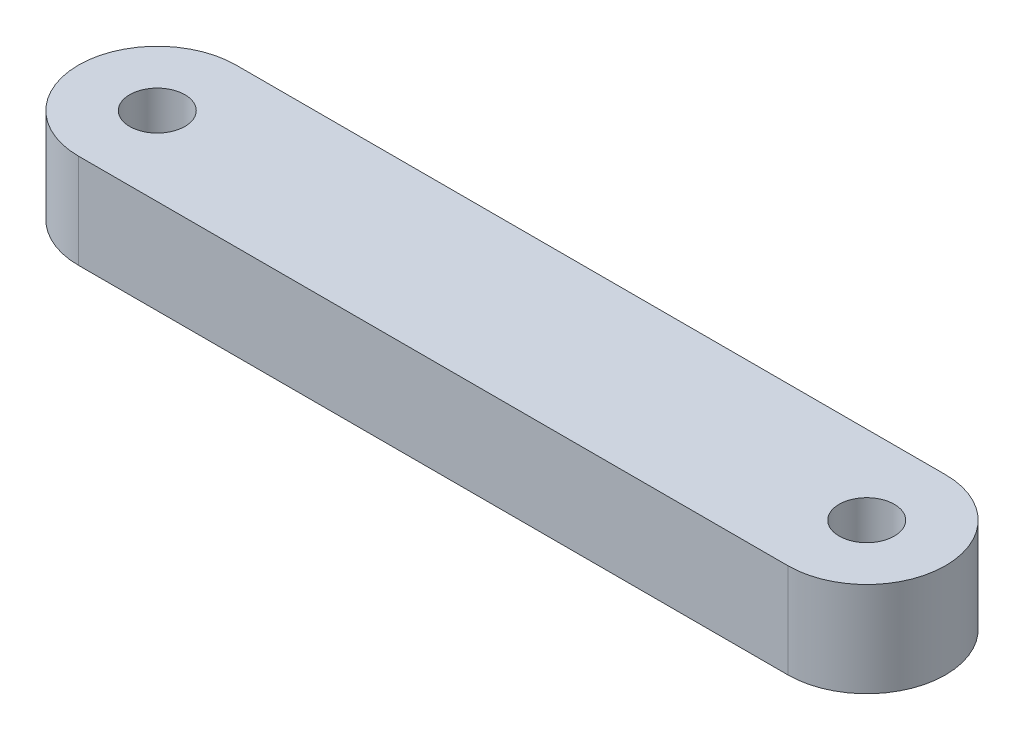
SolidWorks part; units mm, degrees
material "Acrylic (Medium-high impact)"
ref_plane "Front Plane" through (0, 0, 0) normal (0, 0, 1) x (1, 0, 0)
ref_plane "Top Plane" through (0, 0, 0) normal (0, 1, 0) x (1, 0, 0)
ref_plane "Right Plane" through (0, 0, 0) normal (1, 0, 0) x (0, 0, -1)
sketch "Sketch1" plane through (0, 0, 0) normal (0, 1, 0) x (1, 0, 0)
  line L0 (-22.5, 0) -> (22.5, 0) construction
  line L5 (-22.5, 5) -> (22.5, 5)
  line L6 (-22.5, -5) -> (22.5, -5)
  arc A0 (-22.5, 5) -> (-22.5, -5) centre (-22.5, 0) ccw
  arc A1 (22.5, -5) -> (22.5, 5) centre (22.5, 0) ccw
  circle A2 centre (-22.5, 0) radius 1.75
  circle A3 centre (22.5, 0) radius 1.75
  point P2 (0, 0)
  dimension "D3" = 3.5
  dimension "D4" = 3.5
  dimension "D1" = 45
  dimension "D2" = 10
extrude "Boss-Extrude1" add sketch "Sketch1" along normal blind 6
